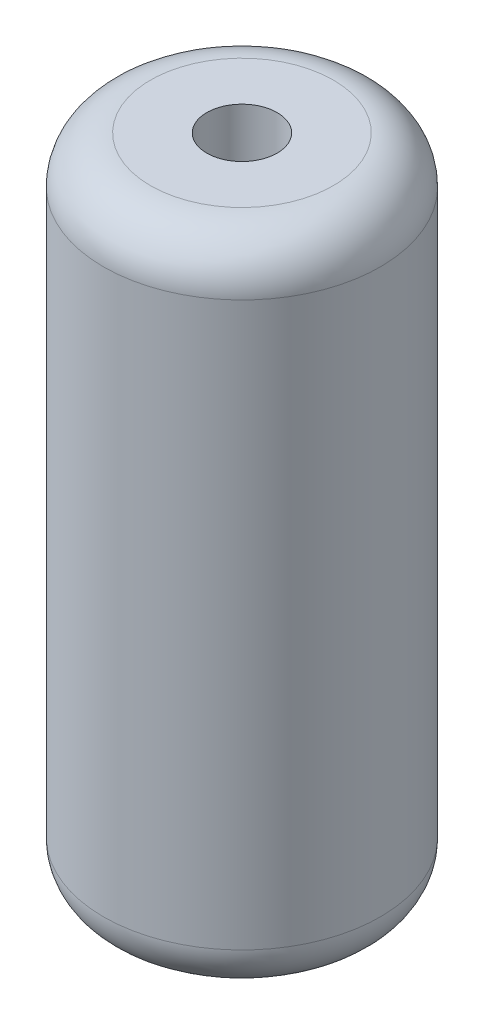
SolidWorks part; units mm, degrees
ref_plane "Front Plane" through (0, 0, 0) normal (0, 0, 1) x (1, 0, 0)
ref_plane "Top Plane" through (0, 0, 0) normal (0, 1, 0) x (1, 0, 0)
ref_plane "Right Plane" through (0, 0, 0) normal (1, 0, 0) x (0, 0, -1)
sketch "Sketch1" plane through (0, 0, 0) normal (0, 1, 0) x (1, 0, 0)
  circle A0 centre (0, 0) radius 29.5
  dimension "D1" = 59
extrude "Boss-Extrude1" add sketch "Sketch1" along normal mid plane 140
fillet "Fillet1" radius 10 2 edges at (0, -70, 29.5) (0, 70, 29.5)
sketch "Sketch2" plane through (0, 70, 0) normal (0, 1, 0) x (1, 0, 0)
  circle A0 centre (0, 0) radius 7.5
extrude "Cut-Extrude1" cut sketch "Sketch2" against normal through all
